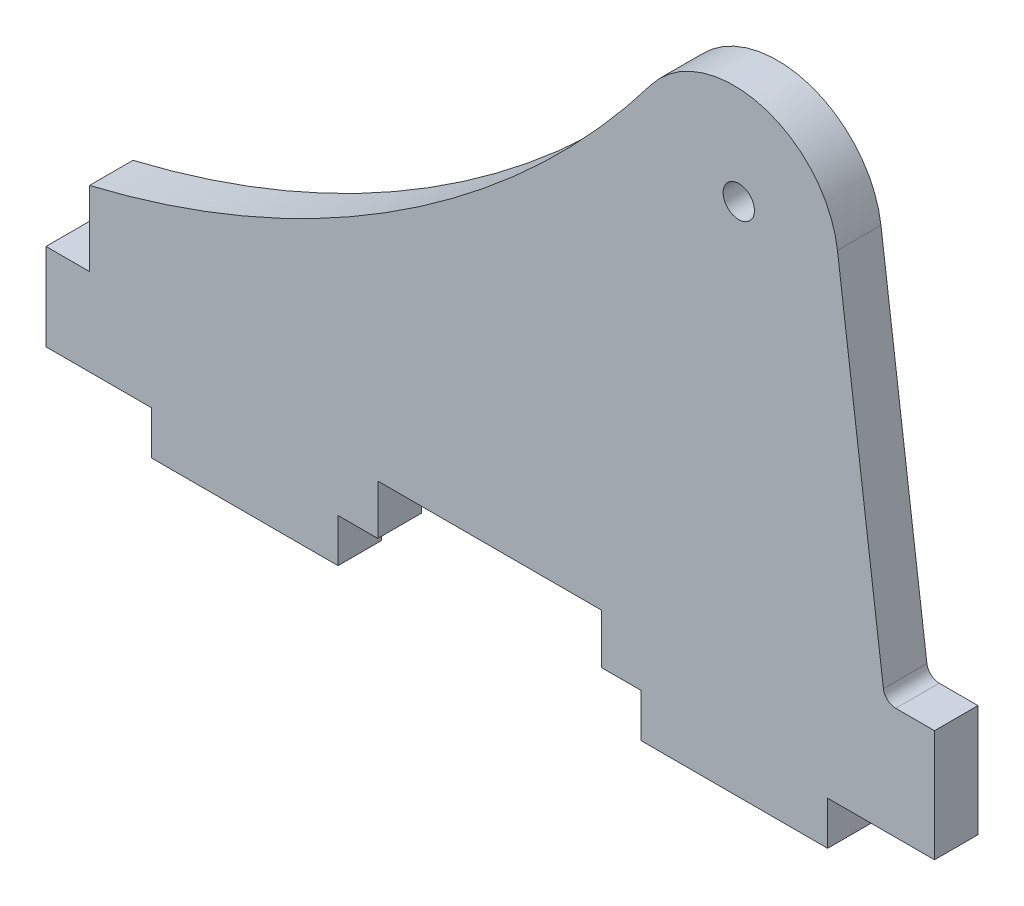
SolidWorks part; units mm, degrees
material "Balsa"
ref_plane "Front Plane" through (0, 0, 0) normal (0, 0, 1) x (1, 0, 0)
ref_plane "Top Plane" through (0, 0, 0) normal (0, 1, 0) x (1, 0, 0)
ref_plane "Right Plane" through (0, 0, 0) normal (1, 0, 0) x (0, 0, -1)
sketch "Sketch1" plane through (0, 0, 0) normal (0, 0, 1) x (1, 0, 0)
  line L0 (0, 10.5) -> (0, 3.5)
  line L1 (0, 3.5) -> (8.5, 3.5)
  line L2 (8.5, 3.5) -> (8.5, 0)
  line L3 (8.5, 0) -> (23.5, 0)
  line L4 (23.5, 0) -> (23.5, 3.5)
  line L8 (47.9, 3.5) -> (47.9, 0)
  line L11 (47.9, 0) -> (62.9, 0)
  line L12 (62.9, 0) -> (62.9, 3.5)
  line L13 (62.9, 3.5) -> (71.5, 3.5)
  line L14 (71.5, 3.5) -> (71.5, 12.5)
  line L15 (71.5, 12.5) -> (67.5, 12.5)
  line L16 (0, 10.5) -> (3.5, 10.5)
  line L17 (3.5, 10.5) -> (3.5, 16.5)
  line L20 (23.5, 3.5) -> (47.9, 3.5)
  line L21 (67.5, 12.5) -> (63.6912, 42.073)
  line L22 (35.7, 3.5) -> (35.7, 37.837) construction
  line L24 (26.7, 3.5) -> (44.7, 3.5)
  line L25 (26.7, 3.5) -> (26.7, 7.5)
  line L26 (26.7, 7.5) -> (44.7, 7.5)
  line L27 (44.7, 3.5) -> (44.7, 7.5)
  arc A1 (63.6912, 42.073) -> (48.6579, 46.0638) centre (55.36, 41) ccw
  arc A2 (3.5, 16.5) -> (48.6579, 46.0638) centre (-15.1713, 94.2906) ccw
  circle A8 centre (55.75, 41.5) radius 1.26
  point P11 (35.7, 7.5)
  dimension "D18" = 16.8
  dimension "D19" = 80
  dimension "D14" = 15.75
  dimension "D1" = 7
  dimension "D2" = 8.5
  dimension "D3" = 3.5
  dimension "D4" = 15
  dimension "D5" = 13
  dimension "D6" = 71.5
  dimension "D7" = 41.5
  dimension "D8" = 18
  dimension "D9" = 4
  dimension "D10" = 8.6
  dimension "D11" = 9
  dimension "D12" = 4
  dimension "D13" = 3.5
extrude "Boss-Extrude1" add sketch "Sketch1" along normal blind 3.5
fillet "Fillet1" radius 1 1 edges at (67.5, 12.5, 1.75)
